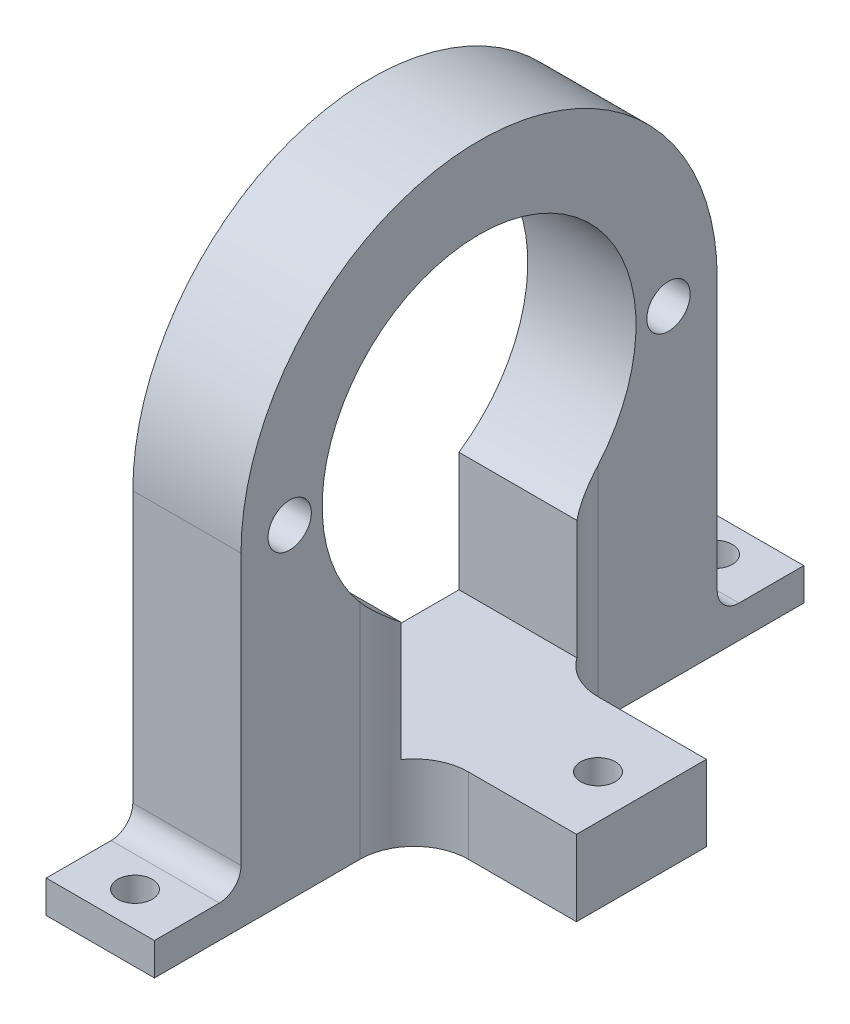
SolidWorks part; units mm, degrees
ref_plane "Front Plane" through (0, 0, 0) normal (0, 0, 1) x (1, 0, 0)
ref_plane "Top Plane" through (0, 0, 0) normal (0, 1, 0) x (1, 0, 0)
ref_plane "Right Plane" through (0, 0, 0) normal (1, 0, 0) x (0, 0, -1)
sketch "Sketch1" plane through (0, 0, 0) normal (1, 0, 0) x (0, 0, -1)
  line L0 (22, -13.5) -> (30, -13.5)
  line L2 (-22, 13.5) -> (-22, -13.5)
  line L4 (22, 13.5) -> (22, -13.5)
  line L6 (-30, -16.5) -> (-30, -13.5)
  line L7 (-30, -13.5) -> (-22, -13.5)
  line L8 (30, -16.5) -> (30, -13.5)
  line L9 (-30, -16.5) -> (30, -16.5)
  arc A0 (22, 13.5) -> (-22, 13.5) centre (0, 13.5) ccw
  circle A1 centre (0, 13.5) radius 14 construction
  point P1 (0, -16.5)
  point P3 (22, 0)
  dimension "D5" = 28
  dimension "D2" = 8
  dimension "D1" = 3
  dimension "D3" = 8
  dimension "D4" = 30
extrude "Boss-Extrude1" add sketch "Sketch1" along normal mid plane 10
sketch "Sketch2" plane through (5, 0, 0) normal (1, 0, 0) x (0, 0, -1)
  line L6 (-8.1394, 1.5) -> (-8.1394, -9.5)
  line L7 (-8.1394, -9.5) -> (8.1394, -9.5)
  line L8 (8.1394, 1.5) -> (8.1394, -9.5)
  arc A2 (8.1394, 1.5) -> (-8.1394, 1.5) centre (0, 13.5) ccw
  point P1 (0, 0)
  point P2 (8.1261, 5.8314)
  point P7 (0, 0)
  dimension "D1" = 14.5
  dimension "D2" = 23
  dimension "D3" = 11
extrude "Cut-Extrude1" cut sketch "Sketch2" against normal through all
sketch "Sketch3" plane through (-5, 0, 0) normal (-1, 0, 0) x (0, 0, 1)
  circle A0 centre (17.5, 13.5) radius 2
  circle A1 centre (-17.5, 13.5) radius 2
  dimension "D1" = 4
extrude "Cut-Extrude2" cut sketch "Sketch3" against normal through all
fillet "Fillet1" radius 2 2 edges at (0, -13.5, -22) (0, -13.5, 22)
sketch "Sketch5" plane through (5, 0, 0) normal (1, 0, 0) x (0, 0, -1)
  line L0 (-30, -16.5) -> (30, -16.5) construction
  line L1 (6, -16.5) -> (-6, -16.5)
  line L2 (6, -16.5) -> (6, -9.5)
  line L3 (6, -9.5) -> (-6, -9.5)
  line L4 (-6, -16.5) -> (-6, -9.5)
  point P6 (0, -9.5)
  point P7 (0, -16.5)
  dimension "D1" = 7
  dimension "D2" = 12
extrude "Boss-Extrude2" add sketch "Sketch5" along normal blind 15
sketch "Sketch4" plane through (0, -13.5, 0) normal (0, 1, 0) x (1, 0, 0)
  line L0 (5, 30) -> (-5, 30) construction
  line L1 (5, -30) -> (-5, -30) construction
  line L2 (0, 26.8) -> (0, 30) construction
  line L3 (0, -26.8) -> (0, -30) construction
  line L5 (20, 6) -> (20, -6) construction
  circle A0 centre (0, 26.8) radius 1.6
  circle A1 centre (0, -26.8) radius 1.6
  circle A2 centre (15.9882, 0) radius 1.6
  point P4 (0, 0)
  point P9 (0, 30)
  point P13 (0, -30)
  point P17 (20, 0)
  dimension "D1" = 3.2
  dimension "D2" = 3.2
extrude "Cut-Extrude3" cut sketch "Sketch4" against normal through all both and the other way through all
fillet "Fillet2" radius 5 2 edges at (5, -13, -6) (5, -13, 6)
